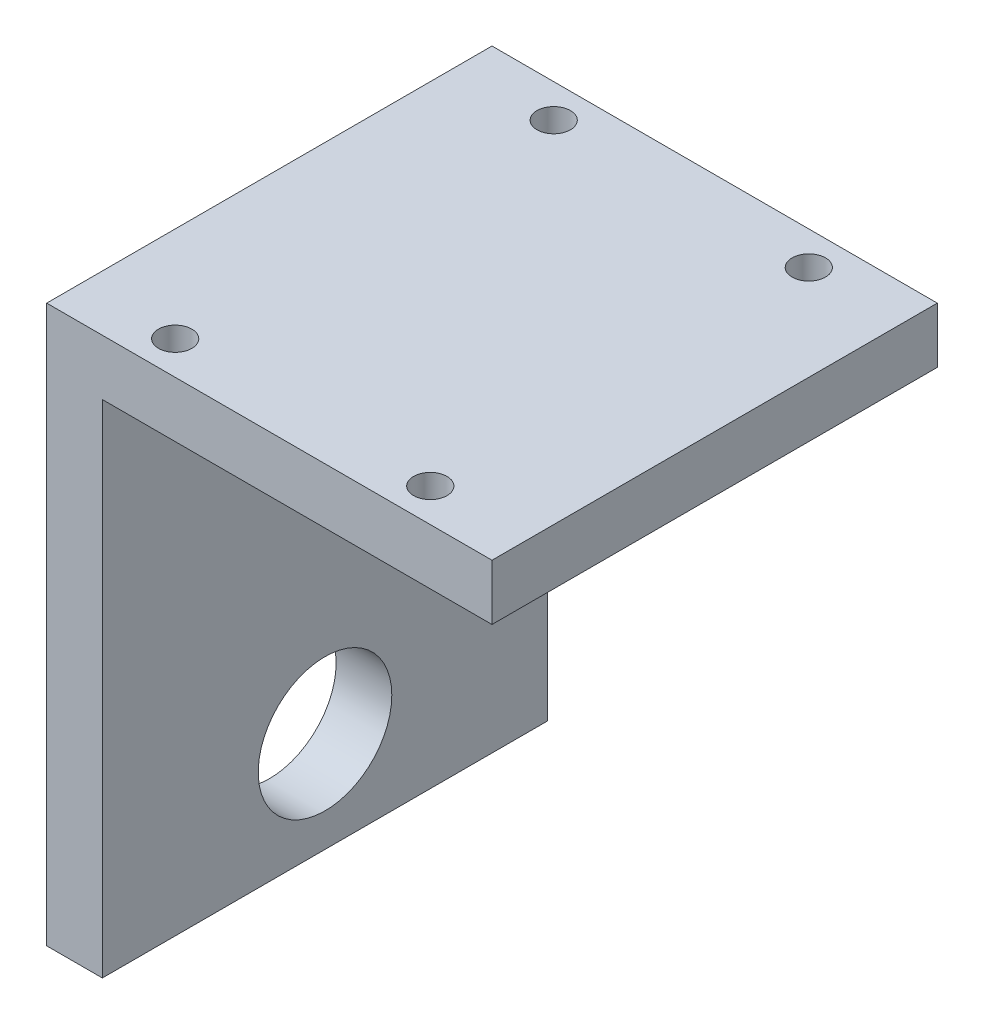
SolidWorks part; units mm, degrees
ref_plane "Front Plane" through (0, 0, 0) normal (0, 0, 1) x (1, 0, 0)
ref_plane "Top Plane" through (0, 0, 0) normal (0, 1, 0) x (1, 0, 0)
ref_plane "Right Plane" through (0, 0, 0) normal (1, 0, 0) x (0, 0, -1)
sketch "Sketch1" plane through (0, 0, 0) normal (0, 1, 0) x (1, 0, 0)
  line L1 (-20, 20) -> (20, 20)
  line L2 (-20, 20) -> (-20, -20)
  line L3 (-20, -20) -> (20, -20)
  line L4 (20, 20) -> (20, -20)
  line L5 (-20, 20) -> (20, -20) construction
  line L6 (-20, -20) -> (20, 20) construction
  point P0 (0, 0)
  dimension "D1" = 40
  dimension "D2" = 40
extrude "Boss-Extrude1" add sketch "Sketch1" along normal blind 5
sketch "Sketch2" plane through (0, 0, 0) normal (0, -1, 0) x (1, 0, 0)
  line L0 (20, -20) -> (-20, -20) construction
  line L1 (-20, 20) -> (-15, 20)
  line L2 (-20, 20) -> (-20, -20)
  line L3 (-20, -20) -> (-15, -20)
  line L4 (-15, 20) -> (-15, -20)
  dimension "D1" = 5
extrude "Boss-Extrude4" add sketch "Sketch2" along normal blind 45
sketch "Sketch6" plane through (-15, 0, 0) normal (1, 0, 0) x (0, 0, -1)
  line L0 (20, -45) -> (-20, -45) construction
  circle A0 centre (0, -36) radius 6
  dimension "D1" = 12
  dimension "D2" = 9
extrude "Cut-Extrude5" cut sketch "Sketch6" against normal through all
sketch "Sketch7" plane through (0, 5, 0) normal (0, 1, 0) x (1, 0, 0)
  line L0 (20, 20) -> (-20, 20) construction
  line L1 (-6.7021, 0) -> (7.8802, 0) construction
  line L2 (0, 5.0164) -> (0, -5.6987) construction
  circle A0 centre (-11.457, 17) radius 1.5
  circle A1 centre (11.457, 17) radius 1.5
  circle A2 centre (11.457, -17) radius 1.5
  circle A3 centre (-11.457, -17) radius 1.5
  dimension "D1" = 3
  dimension "D2" = 3
extrude "Cut-Extrude6" cut sketch "Sketch7" against normal through all
